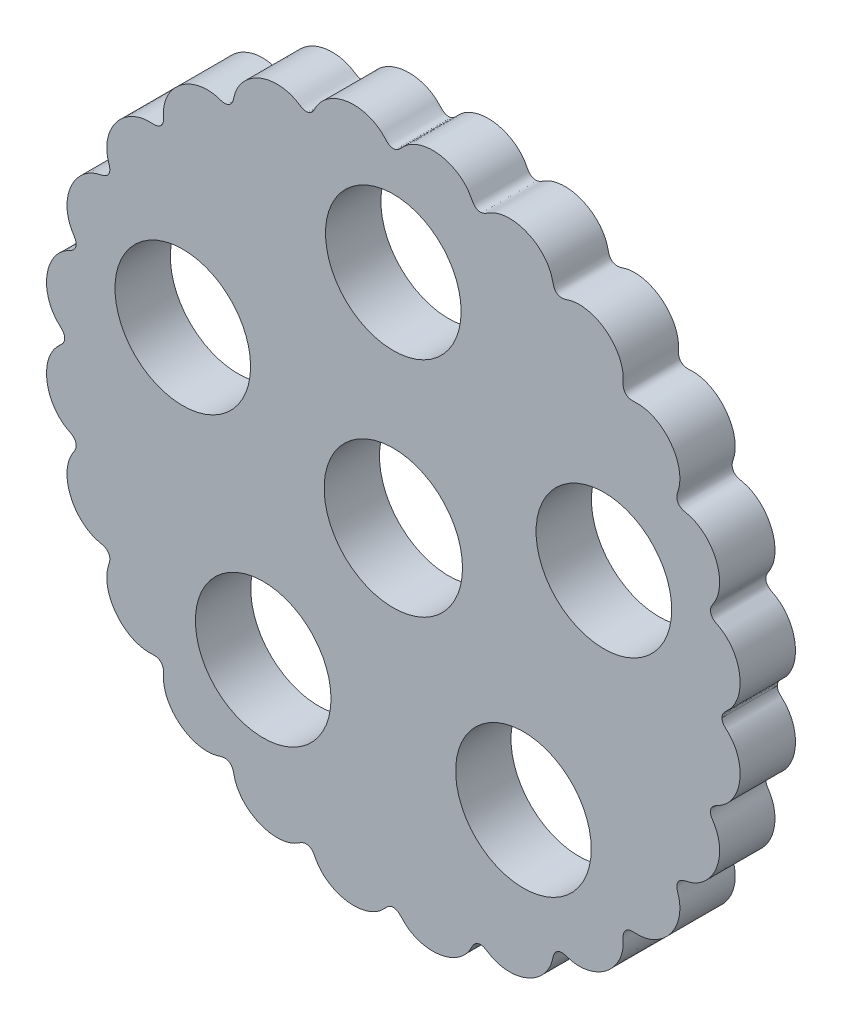
SolidWorks part; units mm, degrees
ref_plane "Plan de face" through (0, 0, 0) normal (0, 0, 1) x (1, 0, 0)
ref_plane "Plan de dessus" through (0, 0, 0) normal (0, 1, 0) x (1, 0, 0)
ref_plane "Plan de droite" through (0, 0, 0) normal (1, 0, 0) x (0, 0, -1)
sketch "Esquisse1" plane through (0, 0, 0) normal (0, 0, 1) x (1, 0, 0)
  line L0 (-1000, 0) -> (49000, 0) construction
  spline S0 degree 4 poles (22.9955, 6.6042) (22.9643, 6.5397) (22.914, 6.4032) (22.9023, 6.1862) (23.0214, 5.9244) (23.2219, 5.7605) (23.4288, 5.659) (23.6594, 5.5306) (23.9059, 5.3649) (24.1666, 5.1353) (24.4254, 4.835) (24.6422, 4.5029) (24.8162, 4.1468) (24.946, 3.7722) (25.0308, 3.385) (25.0698, 2.9906) (25.0624, 2.5943) (25.0079, 2.2017) (24.9068, 1.8224) (24.7781, 1.5066) (24.64, 1.2523) (24.5081, 1.0548) (24.3917, 0.9046) (24.2647, 0.7631) (24.1289, 0.6302) (24.012, 0.5251) (23.9248, 0.4355) (23.8688, 0.3622) (23.8363, 0.3122) (23.8082, 0.2597) (23.7852, 0.2044) (23.7697, 0.1547) (23.76, 0.1121) (23.7533, 0.0661) (23.7501, 0.0228) (23.7495, -0.004) (23.7513, -0.04) (23.7542, -0.0715) (23.7595, -0.1093) (23.7688, -0.1512) (23.7835, -0.1997) (23.8056, -0.2538) (23.8324, -0.3054) (23.8635, -0.3546) (23.9194, -0.4297) (24.009, -0.5227) (24.1313, -0.6322) (24.2737, -0.7721) (24.4392, -0.959) (24.6145, -1.2025) (24.7855, -1.5135) (24.9316, -1.8961) (25.0271, -2.299) (25.0708, -2.7153) (25.0622, -3.1311) (25.0033, -3.5401) (24.8958, -3.9363) (24.7419, -4.314) (24.5445, -4.6645) (24.307, -4.9822) (24.0331, -5.2614) (23.7654, -5.4667) (23.5164, -5.6129) (23.2956, -5.7243) (23.1195, -5.8363) (22.9763, -6.0087) (22.9044, -6.234) (22.925, -6.462) (23.0164, -6.6581) (23.1266, -6.8267) (23.2244, -6.9889) (23.3341, -7.1984) (23.4412, -7.4619) (23.5336, -7.7957) (23.5876, -8.2004) (23.5865, -8.623) (23.5267, -9.0558) (23.3808, -9.5868) (23.1436, -10.0885) (22.8209, -10.5434) (22.4327, -10.9196) (22.1006, -11.1627) (21.7948, -11.3267) (21.5321, -11.4304) (21.3065, -11.4954) (21.1232, -11.5381) (20.9306, -11.5808) (20.7385, -11.6689) (20.5325, -11.8672) (20.4495, -12.16) (20.5219, -12.4298) (20.6167, -12.7241) (20.6818, -13.0067) (20.7176, -13.3406) (20.7046, -13.7295) (20.6405, -14.1156) (20.5273, -14.4945) (20.3673, -14.8595) (20.1602, -15.2112) (19.9061, -15.5428) (19.6059, -15.8469) (19.261, -16.115) (18.8955, -16.3273) (18.5181, -16.4829) (18.1828, -16.5697) (17.9011, -16.6087) (17.6647, -16.6185) (17.4754, -16.6149) (17.2743, -16.6037) (17.0588, -16.6226) (16.851, -16.7187) (16.6918, -16.8937) (16.6141, -17.104) (16.6052, -17.3124) (16.6191, -17.5593) (16.617, -17.8481) (16.5731, -18.1826) (16.4683, -18.5594) (16.3118, -18.9239) (16.107, -19.2701) (15.8569, -19.5923) (15.5674, -19.8834) (15.2427, -20.1389) (14.8869, -20.3543) (14.5046, -20.5246) (14.1078, -20.6433) (13.7035, -20.7081) (13.2985, -20.7166) (12.9508, -20.673) (12.6603, -20.5981) (12.4161, -20.517) (12.2029, -20.4723) (11.9744, -20.5019) (11.768, -20.6211) (11.6281, -20.8042) (11.5602, -21.0112) (11.5084, -21.2632) (11.428, -21.5523) (11.2919, -21.8752) (11.082, -22.2216) (10.8237, -22.5394) (10.5226, -22.8236) (10.1839, -23.0696) (9.8195, -23.2701) (9.4358, -23.4235) (9.039, -23.5286) (8.6349, -23.5841) (8.2327, -23.5884) (7.8388, -23.5416) (7.4601, -23.444) (7.1484, -23.3148) (6.8973, -23.1723) (6.6904, -23.0367) (6.5054, -22.9402) (6.2844, -22.9024) (6.0534, -22.9528) (5.8662, -23.0846) (5.7421, -23.2618) (5.6512, -23.4416) (5.5596, -23.6073) (5.4331, -23.8072) (5.2584, -24.0316) (5.0155, -24.2786) (4.6921, -24.5276) (4.2308, -24.7924) (3.7121, -24.9769) (3.1672, -25.0695) (2.6142, -25.0665) (2.1723, -25.0046) (1.7597, -24.8871) (1.3831, -24.721) (1.0882, -24.5382) (0.867, -24.3625) (0.6979, -24.1997) (0.5693, -24.0623) (0.436, -23.9168) (0.2637, -23.7945) (-0.011, -23.7153) (-0.3061, -23.7898) (-0.5036, -23.9874) (-0.7111, -24.2166) (-0.9232, -24.4143) (-1.1945, -24.6122) (-1.5378, -24.7955) (-1.9042, -24.933) (-2.289, -25.0244) (-2.6851, -25.0684) (-3.0932, -25.0648) (-3.5074, -25.0106) (-3.9209, -24.9026) (-4.3256, -24.738) (-4.6921, -24.5276) (-5.0155, -24.2786) (-5.2584, -24.0316) (-5.4331, -23.8072) (-5.5596, -23.6073) (-5.6512, -23.4416) (-5.7421, -23.2618) (-5.8662, -23.0846) (-6.0534, -22.9528) (-6.2844, -22.9024) (-6.5054, -22.9402) (-6.6904, -23.0367) (-6.8973, -23.1723) (-7.1484, -23.3148) (-7.4601, -23.444) (-7.8388, -23.5416) (-8.2327, -23.5884) (-8.6349, -23.5841) (-9.039, -23.5286) (-9.4358, -23.4235) (-9.8195, -23.2701) (-10.1839, -23.0696) (-10.5226, -22.8236) (-10.8237, -22.5394) (-11.082, -22.2216) (-11.2919, -21.8752) (-11.428, -21.5523) (-11.5084, -21.2632) (-11.5602, -21.0112) (-11.6281, -20.8042) (-11.768, -20.6211) (-11.9744, -20.5019) (-12.2029, -20.4723) (-12.4161, -20.517) (-12.6603, -20.5981) (-12.9508, -20.673) (-13.2985, -20.7166) (-13.7035, -20.7081) (-14.1078, -20.6433) (-14.6048, -20.4946) (-15.1642, -20.2163) (-15.6552, -19.8308) (-16.055, -19.3579) (-16.3118, -18.9239) (-16.4683, -18.5594) (-16.5731, -18.1826) (-16.617, -17.8481) (-16.6191, -17.5593) (-16.6052, -17.3124) (-16.6141, -17.104) (-16.6918, -16.8937) (-16.851, -16.7187) (-17.0588, -16.6226) (-17.2743, -16.6037) (-17.4754, -16.6149) (-17.6647, -16.6185) (-17.9011, -16.6087) (-18.1828, -16.5697) (-18.5181, -16.4829) (-18.8955, -16.3273) (-19.261, -16.1151) (-19.6059, -15.8469) (-19.9061, -15.5428) (-20.1602, -15.2112) (-20.3673, -14.8595) (-20.5273, -14.4945) (-20.6405, -14.1156) (-20.7046, -13.7294) (-20.7175, -13.3407) (-20.6818, -13.0066) (-20.6166, -12.7243) (-20.522, -12.4295) (-20.4494, -12.1605) (-20.5243, -11.8962) (-20.683, -11.7227) (-20.8176, -11.632) (-20.958, -11.5755) (-21.1234, -11.5373) (-21.3064, -11.4958) (-21.5321, -11.4302) (-21.7948, -11.3268) (-22.1006, -11.1626) (-22.4327, -10.9196) (-22.7408, -10.6211) (-23.0153, -10.2693) (-23.2393, -9.8862) (-23.4104, -9.4792) (-23.5267, -9.0558) (-23.5865, -8.623) (-23.5876, -8.2004) (-23.5336, -7.7957) (-23.4412, -7.4619) (-23.3341, -7.1984) (-23.2244, -6.9889) (-23.1266, -6.8267) (-23.0164, -6.6581) (-22.925, -6.462) (-22.9044, -6.234) (-22.9763, -6.0087) (-23.1195, -5.8363) (-23.2956, -5.7243) (-23.5164, -5.6129) (-23.7654, -5.4667) (-24.0331, -5.2614) (-24.307, -4.9822) (-24.5445, -4.6645) (-24.7419, -4.314) (-24.8958, -3.9363) (-25.0033, -3.5401) (-25.0622, -3.1311) (-25.0708, -2.7153) (-25.0271, -2.299) (-24.9316, -1.8961) (-24.7855, -1.5135) (-24.6145, -1.2025) (-24.4393, -0.959) (-24.2737, -0.7721) (-24.1313, -0.6321) (-23.9982, -0.5131) (-23.8995, -0.4084) (-23.8391, -0.3182) (-23.8055, -0.2539) (-23.7835, -0.1997) (-23.7688, -0.1512) (-23.7595, -0.1093) (-23.7542, -0.0715) (-23.7513, -0.04) (-23.7495, -0.0037) (-23.7502, 0.0234) (-23.7534, 0.0677) (-23.7604, 0.1144) (-23.7705, 0.1578) (-23.7867, 0.2087) (-23.8107, 0.2649) (-23.8399, 0.3183) (-23.8736, 0.369) (-23.9317, 0.4432) (-24.0215, 0.5339) (-24.141, 0.6413) (-24.279, 0.7779) (-24.4075, 0.9235) (-24.5249, 1.0783) (-24.6575, 1.2816) (-24.7976, 1.5478) (-24.9275, 1.8824) (-25.0256, 2.2876) (-25.071, 2.7111) (-25.0623, 3.1368) (-25.0002, 3.5582) (-24.8859, 3.9683) (-24.7199, 4.3608) (-24.4999, 4.7349) (-24.2231, 5.0813) (-23.9331, 5.3469) (-23.6469, 5.5411) (-23.3456, 5.7009) (-23.0735, 5.8417) (-22.8982, 6.1368) (-22.9147, 6.4027) (-22.9638, 6.54) (-22.9956, 6.6042) knots 0 0 0 0 0 0.002762 0.005524 0.008057 0.010589 0.012487 0.014385 0.018181 0.021977 0.025773 0.029569 0.033366 0.037162 0.040959 0.044755 0.048552 0.052348 0.056144 0.059791 0.061614 0.063437 0.06526 0.067083 0.068906 0.070729 0.071301 0.071873 0.072445 0.073016 0.073588 0.07416 0.074446 0.074731 0.075303 0.075582 0.075861 0.07614 0.076419 0.076977 0.077535 0.078093 0.078652 0.07921 0.079768 0.081683 0.083599 0.085515 0.08743 0.091261 0.095093 0.099101 0.103109 0.107118 0.111126 0.115032 0.118938 0.122843 0.126749 0.130438 0.134127 0.137815 0.13966 0.141504 0.143638 0.145771 0.148068 0.150364 0.15218 0.153996 0.155812 0.157628 0.16126 0.164892 0.169075 0.173257 0.177439 0.181621 0.190162 0.194433 0.198704 0.20231 0.205917 0.20772 0.209523 0.211327 0.21313 0.215313 0.217496 0.222107 0.223949 0.225791 0.229476 0.23316 0.236844 0.240662 0.24448 0.248298 0.252116 0.256299 0.260481 0.264663 0.268845 0.272477 0.276109 0.277925 0.279741 0.281557 0.283373 0.28567 0.287966 0.2901 0.292233 0.294078 0.295922 0.299611 0.3033 0.306988 0.310894 0.3148 0.318706 0.322612 0.32662 0.330628 0.334637 0.338645 0.342476 0.346307 0.350139 0.352054 0.35397 0.356202 0.358434 0.360667 0.362899 0.364815 0.36673 0.370561 0.374393 0.378224 0.382232 0.386241 0.390249 0.394257 0.398163 0.402069 0.405975 0.40988 0.413569 0.417258 0.420947 0.422791 0.424635 0.426769 0.428902 0.431199 0.433495 0.435311 0.437127 0.438943 0.440759 0.444392 0.448024 0.452206 0.456388 0.464752 0.469023 0.473294 0.477564 0.481835 0.485441 0.489048 0.490851 0.492655 0.494458 0.496261 0.498444 0.500627 0.505239 0.507081 0.508923 0.512607 0.516291 0.519975 0.523793 0.527611 0.53143 0.535248 0.53943 0.543612 0.547794 0.551976 0.555609 0.559241 0.561057 0.562873 0.564689 0.566505 0.568801 0.571098 0.573231 0.575365 0.577209 0.579053 0.582742 0.586431 0.59012 0.594025 0.597931 0.601837 0.605743 0.609751 0.61376 0.617768 0.621776 0.625607 0.629439 0.63327 0.635186 0.637101 0.639333 0.641566 0.643798 0.64603 0.647946 0.649861 0.653693 0.657524 0.661355 0.665364 0.669372 0.677388 0.6852 0.689106 0.693012 0.6967 0.700389 0.704078 0.705922 0.707767 0.7099 0.712034 0.71433 0.716627 0.718443 0.720259 0.722075 0.723891 0.727523 0.731155 0.735337 0.739519 0.743701 0.747884 0.751702 0.75552 0.759338 0.763156 0.76684 0.770525 0.774209 0.776051 0.777893 0.782504 0.784687 0.785779 0.78687 0.788673 0.790477 0.79228 0.794083 0.79769 0.801296 0.805567 0.809838 0.814108 0.818379 0.822561 0.826743 0.830926 0.835108 0.83874 0.842372 0.844188 0.846004 0.84782 0.849636 0.851932 0.854229 0.856362 0.858496 0.86034 0.862185 0.865873 0.869562 0.873251 0.877157 0.881063 0.884968 0.888874 0.892882 0.896891 0.900899 0.904907 0.908739 0.91257 0.914486 0.916401 0.918317 0.920232 0.921349 0.921907 0.922465 0.923023 0.923581 0.92386 0.924139 0.924418 0.924697 0.925281 0.925573 0.925865 0.926449 0.927033 0.927617 0.928201 0.928785 0.929369 0.931232 0.933095 0.934957 0.93682 0.938683 0.940546 0.944272 0.94835 0.952428 0.956506 0.960584 0.964661 0.968739 0.972817 0.976894 0.98129 0.985685 0.987883 0.99008 0.994476 0.997238 1 1 1 1 1 construction
  spline S1 degree 4 poles (23.75, 0) (23.75, -0.0062) (23.7502, -0.0186) (23.7513, -0.04) (23.7542, -0.0715) (23.7595, -0.1093) (23.7688, -0.1512) (23.7835, -0.1997) (23.8056, -0.2538) (23.8324, -0.3054) (23.8635, -0.3546) (23.9194, -0.4297) (24.009, -0.5227) (24.1313, -0.6322) (24.2737, -0.7721) (24.4392, -0.959) (24.6145, -1.2025) (24.7855, -1.5135) (24.9316, -1.8961) (25.0271, -2.299) (25.0708, -2.7153) (25.0622, -3.1311) (25.0033, -3.5401) (24.8958, -3.9363) (24.7419, -4.314) (24.5445, -4.6645) (24.307, -4.9822) (24.0331, -5.2614) (23.7654, -5.4667) (23.5164, -5.6129) (23.2956, -5.7243) (23.1195, -5.8363) (22.9763, -6.0087) (22.9044, -6.234) (22.925, -6.462) (23.0164, -6.6581) (23.1266, -6.8267) (23.2244, -6.9889) (23.3341, -7.1984) (23.4412, -7.4619) (23.5336, -7.7957) (23.5876, -8.2004) (23.5865, -8.623) (23.5267, -9.0558) (23.3808, -9.5868) (23.1436, -10.0885) (22.8209, -10.5434) (22.4327, -10.9196) (22.1006, -11.1627) (21.7948, -11.3267) (21.5321, -11.4304) (21.3065, -11.4954) (21.1232, -11.5381) (20.9306, -11.5808) (20.7385, -11.6689) (20.5325, -11.8672) (20.4495, -12.16) (20.5219, -12.4298) (20.6167, -12.7241) (20.6818, -13.0067) (20.7176, -13.3406) (20.7046, -13.7295) (20.6405, -14.1156) (20.5273, -14.4945) (20.3673, -14.8595) (20.1602, -15.2112) (19.9061, -15.5428) (19.6059, -15.8469) (19.261, -16.115) (18.8955, -16.3273) (18.5181, -16.4829) (18.1828, -16.5697) (17.9011, -16.6087) (17.6647, -16.6185) (17.4754, -16.6149) (17.2743, -16.6037) (17.0588, -16.6226) (16.851, -16.7187) (16.6918, -16.8937) (16.6141, -17.104) (16.6052, -17.3124) (16.6191, -17.5593) (16.617, -17.8481) (16.5731, -18.1826) (16.4683, -18.5594) (16.3118, -18.9239) (16.107, -19.2701) (15.8569, -19.5923) (15.5674, -19.8834) (15.2427, -20.1389) (14.8869, -20.3543) (14.5046, -20.5246) (14.1078, -20.6433) (13.7035, -20.7081) (13.2985, -20.7166) (12.9508, -20.673) (12.6603, -20.5981) (12.4161, -20.517) (12.2029, -20.4723) (11.9744, -20.5019) (11.768, -20.6211) (11.6281, -20.8042) (11.5602, -21.0112) (11.5084, -21.2632) (11.428, -21.5523) (11.2919, -21.8752) (11.082, -22.2216) (10.8237, -22.5394) (10.5226, -22.8236) (10.1839, -23.0696) (9.8195, -23.2701) (9.4358, -23.4235) (9.039, -23.5286) (8.6349, -23.5841) (8.2327, -23.5884) (7.8388, -23.5416) (7.4601, -23.444) (7.1484, -23.3148) (6.8973, -23.1723) (6.6904, -23.0367) (6.5054, -22.9402) (6.2844, -22.9024) (6.0534, -22.9528) (5.8662, -23.0846) (5.7421, -23.2618) (5.6512, -23.4416) (5.5596, -23.6073) (5.4331, -23.8072) (5.2584, -24.0316) (5.0155, -24.2786) (4.6921, -24.5276) (4.2308, -24.7924) (3.7121, -24.9769) (3.1672, -25.0695) (2.6142, -25.0665) (2.1723, -25.0046) (1.7597, -24.8871) (1.3831, -24.721) (1.0882, -24.5382) (0.867, -24.3625) (0.6979, -24.1997) (0.5693, -24.0623) (0.436, -23.9168) (0.2637, -23.7945) (-0.011, -23.7153) (-0.3061, -23.7898) (-0.5036, -23.9874) (-0.7111, -24.2166) (-0.9232, -24.4143) (-1.1945, -24.6122) (-1.5378, -24.7955) (-1.9042, -24.933) (-2.289, -25.0244) (-2.6851, -25.0684) (-3.0932, -25.0648) (-3.5074, -25.0106) (-3.9209, -24.9026) (-4.3256, -24.738) (-4.6921, -24.5276) (-5.0155, -24.2786) (-5.2584, -24.0316) (-5.4331, -23.8072) (-5.5596, -23.6073) (-5.6512, -23.4416) (-5.7421, -23.2618) (-5.8662, -23.0846) (-6.0534, -22.9528) (-6.2844, -22.9024) (-6.5054, -22.9402) (-6.6904, -23.0367) (-6.8973, -23.1723) (-7.1484, -23.3148) (-7.4601, -23.444) (-7.8388, -23.5416) (-8.2327, -23.5884) (-8.6349, -23.5841) (-9.039, -23.5286) (-9.4358, -23.4235) (-9.8195, -23.2701) (-10.1839, -23.0696) (-10.5226, -22.8236) (-10.8237, -22.5394) (-11.082, -22.2216) (-11.2919, -21.8752) (-11.428, -21.5523) (-11.5084, -21.2632) (-11.5602, -21.0112) (-11.6281, -20.8042) (-11.768, -20.6211) (-11.9744, -20.5019) (-12.2029, -20.4723) (-12.4161, -20.517) (-12.6603, -20.5981) (-12.9508, -20.673) (-13.2985, -20.7166) (-13.7035, -20.7081) (-14.1078, -20.6433) (-14.6048, -20.4946) (-15.1642, -20.2163) (-15.6552, -19.8308) (-16.055, -19.3579) (-16.3118, -18.9239) (-16.4683, -18.5594) (-16.5731, -18.1826) (-16.617, -17.8481) (-16.6191, -17.5593) (-16.6052, -17.3124) (-16.6141, -17.104) (-16.6918, -16.8937) (-16.851, -16.7187) (-17.0588, -16.6226) (-17.2743, -16.6037) (-17.4754, -16.6149) (-17.6647, -16.6185) (-17.9011, -16.6087) (-18.1828, -16.5697) (-18.5181, -16.4829) (-18.8955, -16.3273) (-19.261, -16.1151) (-19.6059, -15.8469) (-19.9061, -15.5428) (-20.1602, -15.2112) (-20.3673, -14.8595) (-20.5273, -14.4945) (-20.6405, -14.1156) (-20.7046, -13.7294) (-20.7175, -13.3407) (-20.6818, -13.0066) (-20.6166, -12.7243) (-20.522, -12.4295) (-20.4494, -12.1605) (-20.5243, -11.8962) (-20.683, -11.7227) (-20.8176, -11.632) (-20.958, -11.5755) (-21.1234, -11.5373) (-21.3064, -11.4958) (-21.5321, -11.4302) (-21.7948, -11.3268) (-22.1006, -11.1626) (-22.4327, -10.9196) (-22.7408, -10.6211) (-23.0153, -10.2693) (-23.2393, -9.8862) (-23.4104, -9.4792) (-23.5267, -9.0558) (-23.5865, -8.623) (-23.5876, -8.2004) (-23.5336, -7.7957) (-23.4412, -7.4619) (-23.3341, -7.1984) (-23.2244, -6.9889) (-23.1266, -6.8267) (-23.0164, -6.6581) (-22.925, -6.462) (-22.9044, -6.234) (-22.9763, -6.0087) (-23.1195, -5.8363) (-23.2956, -5.7243) (-23.5164, -5.6129) (-23.7654, -5.4667) (-24.0331, -5.2614) (-24.307, -4.9822) (-24.5445, -4.6645) (-24.7419, -4.314) (-24.8958, -3.9363) (-25.0033, -3.5401) (-25.0622, -3.1311) (-25.0708, -2.7153) (-25.0271, -2.299) (-24.9316, -1.8961) (-24.7855, -1.5135) (-24.6145, -1.2025) (-24.4393, -0.959) (-24.2737, -0.7721) (-24.1313, -0.6321) (-23.9982, -0.5131) (-23.8995, -0.4084) (-23.8391, -0.3182) (-23.8055, -0.2539) (-23.7835, -0.1997) (-23.7688, -0.1512) (-23.7595, -0.1093) (-23.7542, -0.0715) (-23.7513, -0.04) (-23.7502, -0.0186) (-23.75, -0.0062) (-23.75, 0) knots 0.075303 0.075303 0.075303 0.075303 0.075303 0.075582 0.075861 0.07614 0.076419 0.076977 0.077535 0.078093 0.078652 0.07921 0.079768 0.081683 0.083599 0.085515 0.08743 0.091261 0.095093 0.099101 0.103109 0.107118 0.111126 0.115032 0.118938 0.122843 0.126749 0.130438 0.134127 0.137815 0.13966 0.141504 0.143638 0.145771 0.148068 0.150364 0.15218 0.153996 0.155812 0.157628 0.16126 0.164892 0.169075 0.173257 0.177439 0.181621 0.190162 0.194433 0.198704 0.20231 0.205917 0.20772 0.209523 0.211327 0.21313 0.215313 0.217496 0.222107 0.223949 0.225791 0.229476 0.23316 0.236844 0.240662 0.24448 0.248298 0.252116 0.256299 0.260481 0.264663 0.268845 0.272477 0.276109 0.277925 0.279741 0.281557 0.283373 0.28567 0.287966 0.2901 0.292233 0.294078 0.295922 0.299611 0.3033 0.306988 0.310894 0.3148 0.318706 0.322612 0.32662 0.330628 0.334637 0.338645 0.342476 0.346307 0.350139 0.352054 0.35397 0.356202 0.358434 0.360667 0.362899 0.364815 0.36673 0.370561 0.374393 0.378224 0.382232 0.386241 0.390249 0.394257 0.398163 0.402069 0.405975 0.40988 0.413569 0.417258 0.420947 0.422791 0.424635 0.426769 0.428902 0.431199 0.433495 0.435311 0.437127 0.438943 0.440759 0.444392 0.448024 0.452206 0.456388 0.464752 0.469023 0.473294 0.477564 0.481835 0.485441 0.489048 0.490851 0.492655 0.494458 0.496261 0.498444 0.500627 0.505239 0.507081 0.508923 0.512607 0.516291 0.519975 0.523793 0.527611 0.53143 0.535248 0.53943 0.543612 0.547794 0.551976 0.555609 0.559241 0.561057 0.562873 0.564689 0.566505 0.568801 0.571098 0.573231 0.575365 0.577209 0.579053 0.582742 0.586431 0.59012 0.594025 0.597931 0.601837 0.605743 0.609751 0.61376 0.617768 0.621776 0.625607 0.629439 0.63327 0.635186 0.637101 0.639333 0.641566 0.643798 0.64603 0.647946 0.649861 0.653693 0.657524 0.661355 0.665364 0.669372 0.677388 0.6852 0.689106 0.693012 0.6967 0.700389 0.704078 0.705922 0.707767 0.7099 0.712034 0.71433 0.716627 0.718443 0.720259 0.722075 0.723891 0.727523 0.731155 0.735337 0.739519 0.743701 0.747884 0.751702 0.75552 0.759338 0.763156 0.76684 0.770525 0.774209 0.776051 0.777893 0.782504 0.784687 0.785779 0.78687 0.788673 0.790477 0.79228 0.794083 0.79769 0.801296 0.805567 0.809838 0.814108 0.818379 0.822561 0.826743 0.830926 0.835108 0.83874 0.842372 0.844188 0.846004 0.84782 0.849636 0.851932 0.854229 0.856362 0.858496 0.86034 0.862185 0.865873 0.869562 0.873251 0.877157 0.881063 0.884968 0.888874 0.892882 0.896891 0.900899 0.904907 0.908739 0.91257 0.914486 0.916401 0.918317 0.920232 0.921349 0.921907 0.922465 0.923023 0.923581 0.92386 0.924139 0.924418 0.924697 0.924697 0.924697 0.924697 0.924697 construction
  spline S2 degree 4 poles (23.75, 0) (23.75, 0.0062) (23.7502, 0.0186) (23.7513, 0.04) (23.7542, 0.0715) (23.7595, 0.1093) (23.7688, 0.1512) (23.7835, 0.1997) (23.8056, 0.2538) (23.8324, 0.3054) (23.8635, 0.3546) (23.9194, 0.4297) (24.009, 0.5227) (24.1313, 0.6322) (24.2737, 0.7721) (24.4392, 0.959) (24.6145, 1.2025) (24.7855, 1.5135) (24.9316, 1.8961) (25.0271, 2.299) (25.0708, 2.7153) (25.0622, 3.1311) (25.0033, 3.5401) (24.8958, 3.9363) (24.7419, 4.314) (24.5445, 4.6645) (24.307, 4.9822) (24.0331, 5.2614) (23.7654, 5.4667) (23.5164, 5.6129) (23.2956, 5.7243) (23.1195, 5.8363) (22.9763, 6.0087) (22.9044, 6.234) (22.925, 6.462) (23.0164, 6.6581) (23.1266, 6.8267) (23.2244, 6.9889) (23.3341, 7.1984) (23.4412, 7.4619) (23.5336, 7.7957) (23.5876, 8.2004) (23.5865, 8.623) (23.5267, 9.0558) (23.3808, 9.5868) (23.1436, 10.0885) (22.8209, 10.5434) (22.4327, 10.9196) (22.1006, 11.1627) (21.7948, 11.3267) (21.5321, 11.4304) (21.3065, 11.4954) (21.1232, 11.5381) (20.9306, 11.5808) (20.7385, 11.6689) (20.5325, 11.8672) (20.4495, 12.16) (20.5219, 12.4298) (20.6167, 12.7241) (20.6818, 13.0067) (20.7176, 13.3406) (20.7046, 13.7295) (20.6405, 14.1156) (20.5273, 14.4945) (20.3673, 14.8595) (20.1602, 15.2112) (19.9061, 15.5428) (19.6059, 15.8469) (19.261, 16.115) (18.8955, 16.3273) (18.5181, 16.4829) (18.1828, 16.5697) (17.9011, 16.6087) (17.6647, 16.6185) (17.4754, 16.6149) (17.2743, 16.6037) (17.0588, 16.6226) (16.851, 16.7187) (16.6918, 16.8937) (16.6141, 17.104) (16.6052, 17.3124) (16.6191, 17.5593) (16.617, 17.8481) (16.5731, 18.1826) (16.4683, 18.5594) (16.3118, 18.9239) (16.107, 19.2701) (15.8569, 19.5923) (15.5674, 19.8834) (15.2427, 20.1389) (14.8869, 20.3543) (14.5046, 20.5246) (14.1078, 20.6433) (13.7035, 20.7081) (13.2985, 20.7166) (12.9508, 20.673) (12.6603, 20.5981) (12.4161, 20.517) (12.2029, 20.4723) (11.9744, 20.5019) (11.768, 20.6211) (11.6281, 20.8042) (11.5602, 21.0112) (11.5084, 21.2632) (11.428, 21.5523) (11.2919, 21.8752) (11.082, 22.2216) (10.8237, 22.5394) (10.5226, 22.8236) (10.1839, 23.0696) (9.8195, 23.2701) (9.4358, 23.4235) (9.039, 23.5286) (8.6349, 23.5841) (8.2327, 23.5884) (7.8388, 23.5416) (7.4601, 23.444) (7.1484, 23.3148) (6.8973, 23.1723) (6.6904, 23.0367) (6.5054, 22.9402) (6.2844, 22.9024) (6.0534, 22.9528) (5.8662, 23.0846) (5.7421, 23.2618) (5.6512, 23.4416) (5.5596, 23.6073) (5.4331, 23.8072) (5.2584, 24.0316) (5.0155, 24.2786) (4.6921, 24.5276) (4.2308, 24.7924) (3.7121, 24.9769) (3.1672, 25.0695) (2.6142, 25.0665) (2.1723, 25.0046) (1.7597, 24.8871) (1.3831, 24.721) (1.0882, 24.5382) (0.867, 24.3625) (0.6979, 24.1997) (0.5693, 24.0623) (0.436, 23.9168) (0.2637, 23.7945) (-0.011, 23.7153) (-0.3061, 23.7898) (-0.5036, 23.9874) (-0.7111, 24.2166) (-0.9232, 24.4143) (-1.1945, 24.6122) (-1.5378, 24.7955) (-1.9042, 24.933) (-2.289, 25.0244) (-2.6851, 25.0684) (-3.0932, 25.0648) (-3.5074, 25.0106) (-3.9209, 24.9026) (-4.3256, 24.738) (-4.6921, 24.5276) (-5.0155, 24.2786) (-5.2584, 24.0316) (-5.4331, 23.8072) (-5.5596, 23.6073) (-5.6512, 23.4416) (-5.7421, 23.2618) (-5.8662, 23.0846) (-6.0534, 22.9528) (-6.2844, 22.9024) (-6.5054, 22.9402) (-6.6904, 23.0367) (-6.8973, 23.1723) (-7.1484, 23.3148) (-7.4601, 23.444) (-7.8388, 23.5416) (-8.2327, 23.5884) (-8.6349, 23.5841) (-9.039, 23.5286) (-9.4358, 23.4235) (-9.8195, 23.2701) (-10.1839, 23.0696) (-10.5226, 22.8236) (-10.8237, 22.5394) (-11.082, 22.2216) (-11.2919, 21.8752) (-11.428, 21.5523) (-11.5084, 21.2632) (-11.5602, 21.0112) (-11.6281, 20.8042) (-11.768, 20.6211) (-11.9744, 20.5019) (-12.2029, 20.4723) (-12.4161, 20.517) (-12.6603, 20.5981) (-12.9508, 20.673) (-13.2985, 20.7166) (-13.7035, 20.7081) (-14.1078, 20.6433) (-14.6048, 20.4946) (-15.1642, 20.2163) (-15.6552, 19.8308) (-16.055, 19.3579) (-16.3118, 18.9239) (-16.4683, 18.5594) (-16.5731, 18.1826) (-16.617, 17.8481) (-16.6191, 17.5593) (-16.6052, 17.3124) (-16.6141, 17.104) (-16.6918, 16.8937) (-16.851, 16.7187) (-17.0588, 16.6226) (-17.2743, 16.6037) (-17.4754, 16.6149) (-17.6647, 16.6185) (-17.9011, 16.6087) (-18.1828, 16.5697) (-18.5181, 16.4829) (-18.8955, 16.3273) (-19.261, 16.1151) (-19.6059, 15.8469) (-19.9061, 15.5428) (-20.1602, 15.2112) (-20.3673, 14.8595) (-20.5273, 14.4945) (-20.6405, 14.1156) (-20.7046, 13.7294) (-20.7175, 13.3407) (-20.6818, 13.0066) (-20.6166, 12.7243) (-20.522, 12.4295) (-20.4494, 12.1605) (-20.5243, 11.8962) (-20.683, 11.7227) (-20.8176, 11.632) (-20.958, 11.5755) (-21.1234, 11.5373) (-21.3064, 11.4958) (-21.5321, 11.4302) (-21.7948, 11.3268) (-22.1006, 11.1626) (-22.4327, 10.9196) (-22.7408, 10.6211) (-23.0153, 10.2693) (-23.2393, 9.8862) (-23.4104, 9.4792) (-23.5267, 9.0558) (-23.5865, 8.623) (-23.5876, 8.2004) (-23.5336, 7.7957) (-23.4412, 7.4619) (-23.3341, 7.1984) (-23.2244, 6.9889) (-23.1266, 6.8267) (-23.0164, 6.6581) (-22.925, 6.462) (-22.9044, 6.234) (-22.9763, 6.0087) (-23.1195, 5.8363) (-23.2956, 5.7243) (-23.5164, 5.6129) (-23.7654, 5.4667) (-24.0331, 5.2614) (-24.307, 4.9822) (-24.5445, 4.6645) (-24.7419, 4.314) (-24.8958, 3.9363) (-25.0033, 3.5401) (-25.0622, 3.1311) (-25.0708, 2.7153) (-25.0271, 2.299) (-24.9316, 1.8961) (-24.7855, 1.5135) (-24.6145, 1.2025) (-24.4393, 0.959) (-24.2737, 0.7721) (-24.1313, 0.6321) (-23.9982, 0.5131) (-23.8995, 0.4084) (-23.8391, 0.3182) (-23.8055, 0.2539) (-23.7835, 0.1997) (-23.7688, 0.1512) (-23.7595, 0.1093) (-23.7542, 0.0715) (-23.7513, 0.04) (-23.7502, 0.0186) (-23.75, 0.0062) (-23.75, 0) knots 0.075303 0.075303 0.075303 0.075303 0.075303 0.075582 0.075861 0.07614 0.076419 0.076977 0.077535 0.078093 0.078652 0.07921 0.079768 0.081683 0.083599 0.085515 0.08743 0.091261 0.095093 0.099101 0.103109 0.107118 0.111126 0.115032 0.118938 0.122843 0.126749 0.130438 0.134127 0.137815 0.13966 0.141504 0.143638 0.145771 0.148068 0.150364 0.15218 0.153996 0.155812 0.157628 0.16126 0.164892 0.169075 0.173257 0.177439 0.181621 0.190162 0.194433 0.198704 0.20231 0.205917 0.20772 0.209523 0.211327 0.21313 0.215313 0.217496 0.222107 0.223949 0.225791 0.229476 0.23316 0.236844 0.240662 0.24448 0.248298 0.252116 0.256299 0.260481 0.264663 0.268845 0.272477 0.276109 0.277925 0.279741 0.281557 0.283373 0.28567 0.287966 0.2901 0.292233 0.294078 0.295922 0.299611 0.3033 0.306988 0.310894 0.3148 0.318706 0.322612 0.32662 0.330628 0.334637 0.338645 0.342476 0.346307 0.350139 0.352054 0.35397 0.356202 0.358434 0.360667 0.362899 0.364815 0.36673 0.370561 0.374393 0.378224 0.382232 0.386241 0.390249 0.394257 0.398163 0.402069 0.405975 0.40988 0.413569 0.417258 0.420947 0.422791 0.424635 0.426769 0.428902 0.431199 0.433495 0.435311 0.437127 0.438943 0.440759 0.444392 0.448024 0.452206 0.456388 0.464752 0.469023 0.473294 0.477564 0.481835 0.485441 0.489048 0.490851 0.492655 0.494458 0.496261 0.498444 0.500627 0.505239 0.507081 0.508923 0.512607 0.516291 0.519975 0.523793 0.527611 0.53143 0.535248 0.53943 0.543612 0.547794 0.551976 0.555609 0.559241 0.561057 0.562873 0.564689 0.566505 0.568801 0.571098 0.573231 0.575365 0.577209 0.579053 0.582742 0.586431 0.59012 0.594025 0.597931 0.601837 0.605743 0.609751 0.61376 0.617768 0.621776 0.625607 0.629439 0.63327 0.635186 0.637101 0.639333 0.641566 0.643798 0.64603 0.647946 0.649861 0.653693 0.657524 0.661355 0.665364 0.669372 0.677388 0.6852 0.689106 0.693012 0.6967 0.700389 0.704078 0.705922 0.707767 0.7099 0.712034 0.71433 0.716627 0.718443 0.720259 0.722075 0.723891 0.727523 0.731155 0.735337 0.739519 0.743701 0.747884 0.751702 0.75552 0.759338 0.763156 0.76684 0.770525 0.774209 0.776051 0.777893 0.782504 0.784687 0.785779 0.78687 0.788673 0.790477 0.79228 0.794083 0.79769 0.801296 0.805567 0.809838 0.814108 0.818379 0.822561 0.826743 0.830926 0.835108 0.83874 0.842372 0.844188 0.846004 0.84782 0.849636 0.851932 0.854229 0.856362 0.858496 0.86034 0.862185 0.865873 0.869562 0.873251 0.877157 0.881063 0.884968 0.888874 0.892882 0.896891 0.900899 0.904907 0.908739 0.91257 0.914486 0.916401 0.918317 0.920232 0.921349 0.921907 0.922465 0.923023 0.923581 0.92386 0.924139 0.924418 0.924697 0.924697 0.924697 0.924697 0.924697 construction
  spline S3 degree 1 poles (23.75, 0) (-23.75, 0) knots 0 0 1 1 construction
  spline S4 degree 1 poles (23.75, 0) (-23.75, 0) knots 0 0 1 1 construction
  spline S5 degree 3 poles (23.75, 0) (23.75, 0.1137) (23.8219, 0.3453) (24.0779, 0.5835) (24.3269, 0.822) (24.6131, 1.1852) (24.88, 1.7) (25.0523, 2.3737) (25.0798, 3.068) (24.9658, 3.7534) (24.714, 4.4011) (24.3299, 4.981) (23.9042, 5.3758) (23.5122, 5.6193) (23.1973, 5.7658) (22.9497, 6.022) (22.891, 6.382) (23.0374, 6.7027) (23.2955, 7.0836) (23.5106, 7.6247) (23.6065, 8.3133) (23.5489, 9.0061) (23.3498, 9.6718) (23.0199, 10.2833) (22.5707, 10.8139) (22.0159, 11.233) (21.4813, 11.4634) (21.0294, 11.5505) (20.6992, 11.6737) (20.486, 11.9701) (20.4801, 12.3255) (20.599, 12.6524) (20.7041, 13.1016) (20.726, 13.6818) (20.5875, 14.3634) (20.3076, 14.9994) (19.9035, 15.5647) (19.3931, 16.0362) (18.7949, 16.3908) (18.2422, 16.566) (17.7829, 16.6205) (17.4383, 16.613) (17.0884, 16.6008) (16.7684, 16.7684) (16.6008, 17.0884) (16.6129, 17.4383) (16.6205, 17.7829) (16.566, 18.2422) (16.3908, 18.7949) (16.0362, 19.3931) (15.5647, 19.9035) (14.9995, 20.3075) (14.3634, 20.5875) (13.6817, 20.726) (13.1016, 20.7041) (12.6522, 20.5991) (12.3259, 20.48) (11.9697, 20.4861) (11.6737, 20.6992) (11.5504, 21.0295) (11.4637, 21.4813) (11.233, 22.016) (10.814, 22.5707) (10.2832, 23.0199) (9.6718, 23.3498) (9.0061, 23.5489) (8.3132, 23.6065) (7.6247, 23.5105) (7.0835, 23.2956) (6.7027, 23.0375) (6.3819, 22.8911) (6.022, 22.9497) (5.7658, 23.1973) (5.6193, 23.5123) (5.3758, 23.9042) (4.981, 24.3299) (4.4011, 24.714) (3.7534, 24.9658) (3.068, 25.0798) (2.3737, 25.0523) (1.7, 24.88) (1.1852, 24.6131) (0.822, 24.3269) (0.5834, 24.078) (0.3446, 23.8219) (0.0001, 23.714) (-0.3442, 23.8218) (-0.5845, 24.0782) (-0.8215, 24.3267) (-1.1856, 24.6132) (-1.6999, 24.88) (-2.3737, 25.0523) (-3.068, 25.0798) (-3.7534, 24.9658) (-4.4011, 24.714) (-4.981, 24.3299) (-5.3758, 23.9042) (-5.6193, 23.5123) (-5.7658, 23.1973) (-6.022, 22.9497) (-6.3819, 22.8911) (-6.7027, 23.0375) (-7.0835, 23.2956) (-7.6247, 23.5105) (-8.3132, 23.6065) (-9.0061, 23.5489) (-9.6718, 23.3498) (-10.2832, 23.0199) (-10.814, 22.5707) (-11.233, 22.016) (-11.4637, 21.4813) (-11.5504, 21.0295) (-11.6737, 20.6992) (-11.9697, 20.4861) (-12.3259, 20.48) (-12.6522, 20.5991) (-13.1016, 20.7041) (-13.6817, 20.726) (-14.3634, 20.5875) (-14.9995, 20.3075) (-15.5647, 19.9035) (-16.0362, 19.3931) (-16.3908, 18.7949) (-16.566, 18.2422) (-16.6205, 17.7829) (-16.6129, 17.4383) (-16.6008, 17.0884) (-16.7684, 16.7684) (-17.0884, 16.6008) (-17.4383, 16.613) (-17.7829, 16.6205) (-18.2422, 16.566) (-18.7949, 16.3908) (-19.3931, 16.0362) (-19.9035, 15.5647) (-20.3076, 14.9994) (-20.5875, 14.3634) (-20.726, 13.6818) (-20.7041, 13.1016) (-20.599, 12.6524) (-20.48, 12.3256) (-20.486, 11.97) (-20.6991, 11.6738) (-21.0294, 11.5505) (-21.4813, 11.4636) (-22.0159, 11.233) (-22.5707, 10.814) (-23.0199, 10.2833) (-23.3498, 9.6718) (-23.5489, 9.0061) (-23.6065, 8.3133) (-23.5106, 7.6247) (-23.2955, 7.0836) (-23.0374, 6.7027) (-22.891, 6.382) (-22.9497, 6.022) (-23.1973, 5.7658) (-23.5122, 5.6193) (-23.9042, 5.3758) (-24.3299, 4.981) (-24.714, 4.4011) (-24.9658, 3.7534) (-25.0798, 3.068) (-25.0523, 2.3737) (-24.88, 1.7) (-24.6131, 1.1852) (-24.3269, 0.822) (-24.0779, 0.5835) (-23.8219, 0.3453) (-23.75, 0.1137) (-23.75, 0) knots 0.075303 0.075303 0.075303 0.075303 0.078621 0.081939 0.085257 0.088575 0.095211 0.101847 0.108483 0.115118 0.121754 0.12839 0.135026 0.138344 0.141662 0.14498 0.148298 0.151616 0.154934 0.16157 0.168206 0.174841 0.181477 0.188113 0.194749 0.201385 0.208021 0.211339 0.214657 0.217975 0.221293 0.224611 0.227929 0.234564 0.2412 0.247836 0.254472 0.261108 0.267744 0.27438 0.277698 0.281016 0.284334 0.287652 0.29097 0.294287 0.297605 0.300923 0.307559 0.314195 0.320831 0.327467 0.334103 0.340739 0.347375 0.350693 0.35401 0.357328 0.360646 0.363964 0.367282 0.373918 0.380554 0.38719 0.393826 0.400462 0.407098 0.413733 0.420369 0.423687 0.427005 0.430323 0.433641 0.436959 0.440277 0.446913 0.453549 0.460185 0.466821 0.473456 0.480092 0.486728 0.490046 0.493364 0.496682 0.5 0.503318 0.506636 0.509954 0.513272 0.519908 0.526544 0.533179 0.539815 0.546451 0.553087 0.559723 0.563041 0.566359 0.569677 0.572995 0.576313 0.579631 0.586267 0.592902 0.599538 0.606174 0.61281 0.619446 0.626082 0.632718 0.636036 0.639354 0.642672 0.64599 0.649308 0.652625 0.659261 0.665897 0.672533 0.679169 0.685805 0.692441 0.699077 0.702395 0.705713 0.709031 0.712348 0.715666 0.718984 0.722302 0.72562 0.732256 0.738892 0.745528 0.752164 0.7588 0.765436 0.772071 0.775389 0.778707 0.782025 0.785343 0.788661 0.791979 0.798615 0.805251 0.811887 0.818523 0.825159 0.831794 0.83843 0.845066 0.848384 0.851702 0.85502 0.858338 0.861656 0.864974 0.87161 0.878246 0.884882 0.891518 0.898153 0.904789 0.911425 0.914743 0.918061 0.921379 0.924697 0.924697 0.924697 0.924697
  spline S6 degree 3 poles (-23.75, 0) (-23.75, -0.1137) (-23.8219, -0.3453) (-24.0779, -0.5835) (-24.3269, -0.822) (-24.6131, -1.1852) (-24.88, -1.7) (-25.0523, -2.3737) (-25.0798, -3.068) (-24.9658, -3.7534) (-24.714, -4.4011) (-24.3299, -4.981) (-23.9042, -5.3758) (-23.5122, -5.6193) (-23.1973, -5.7658) (-22.9497, -6.022) (-22.891, -6.382) (-23.0374, -6.7027) (-23.2955, -7.0836) (-23.5106, -7.6247) (-23.6065, -8.3133) (-23.5489, -9.0061) (-23.3498, -9.6718) (-23.0199, -10.2833) (-22.5707, -10.814) (-22.0159, -11.233) (-21.4813, -11.4636) (-21.0294, -11.5505) (-20.6991, -11.6738) (-20.486, -11.97) (-20.48, -12.3256) (-20.599, -12.6524) (-20.7041, -13.1016) (-20.726, -13.6818) (-20.5875, -14.3634) (-20.3076, -14.9994) (-19.9035, -15.5647) (-19.3931, -16.0362) (-18.7949, -16.3908) (-18.2422, -16.566) (-17.7829, -16.6205) (-17.4383, -16.613) (-17.0884, -16.6008) (-16.7684, -16.7684) (-16.6008, -17.0884) (-16.6129, -17.4383) (-16.6205, -17.7829) (-16.566, -18.2422) (-16.3908, -18.7949) (-16.0362, -19.3931) (-15.5647, -19.9035) (-14.9995, -20.3075) (-14.3634, -20.5875) (-13.6817, -20.726) (-13.1016, -20.7041) (-12.6522, -20.5991) (-12.3259, -20.48) (-11.9697, -20.4861) (-11.6737, -20.6992) (-11.5504, -21.0295) (-11.4637, -21.4813) (-11.233, -22.016) (-10.814, -22.5707) (-10.2832, -23.0199) (-9.6718, -23.3498) (-9.0061, -23.5489) (-8.3132, -23.6065) (-7.6247, -23.5105) (-7.0835, -23.2956) (-6.7027, -23.0375) (-6.3819, -22.8911) (-6.022, -22.9497) (-5.7658, -23.1973) (-5.6193, -23.5123) (-5.3758, -23.9042) (-4.981, -24.3299) (-4.4011, -24.714) (-3.7534, -24.9658) (-3.068, -25.0798) (-2.3737, -25.0523) (-1.6999, -24.88) (-1.1856, -24.6132) (-0.8215, -24.3267) (-0.5845, -24.0782) (-0.3442, -23.8218) (0.0001, -23.714) (0.3446, -23.8219) (0.5834, -24.078) (0.822, -24.3269) (1.1852, -24.6131) (1.7, -24.88) (2.3737, -25.0523) (3.068, -25.0798) (3.7534, -24.9658) (4.4011, -24.714) (4.981, -24.3299) (5.3758, -23.9042) (5.6193, -23.5123) (5.7658, -23.1973) (6.022, -22.9497) (6.3819, -22.8911) (6.7027, -23.0375) (7.0835, -23.2956) (7.6247, -23.5105) (8.3132, -23.6065) (9.0061, -23.5489) (9.6718, -23.3498) (10.2832, -23.0199) (10.814, -22.5707) (11.233, -22.016) (11.4637, -21.4813) (11.5504, -21.0295) (11.6737, -20.6992) (11.9697, -20.4861) (12.3259, -20.48) (12.6522, -20.5991) (13.1016, -20.7041) (13.6817, -20.726) (14.3634, -20.5875) (14.9995, -20.3075) (15.5647, -19.9035) (16.0362, -19.3931) (16.3908, -18.7949) (16.566, -18.2422) (16.6205, -17.7829) (16.6129, -17.4383) (16.6008, -17.0884) (16.7684, -16.7684) (17.0884, -16.6008) (17.4383, -16.613) (17.7829, -16.6205) (18.2422, -16.566) (18.7949, -16.3908) (19.3931, -16.0362) (19.9035, -15.5647) (20.3076, -14.9994) (20.5875, -14.3634) (20.726, -13.6818) (20.7041, -13.1016) (20.599, -12.6524) (20.4801, -12.3255) (20.486, -11.9701) (20.6992, -11.6737) (21.0294, -11.5505) (21.4813, -11.4634) (22.0159, -11.233) (22.5707, -10.8139) (23.0199, -10.2833) (23.3498, -9.6718) (23.5489, -9.0061) (23.6065, -8.3133) (23.5106, -7.6247) (23.2955, -7.0836) (23.0374, -6.7027) (22.891, -6.382) (22.9497, -6.022) (23.1973, -5.7658) (23.5122, -5.6193) (23.9042, -5.3758) (24.3299, -4.981) (24.714, -4.4011) (24.9658, -3.7534) (25.0798, -3.068) (25.0523, -2.3737) (24.88, -1.7) (24.6131, -1.1852) (24.3269, -0.822) (24.0779, -0.5835) (23.8219, -0.3453) (23.75, -0.1137) (23.75, 0) knots 0.075303 0.075303 0.075303 0.075303 0.078621 0.081939 0.085257 0.088575 0.095211 0.101847 0.108483 0.115118 0.121754 0.12839 0.135026 0.138344 0.141662 0.14498 0.148298 0.151616 0.154934 0.16157 0.168206 0.174841 0.181477 0.188113 0.194749 0.201385 0.208021 0.211339 0.214657 0.217975 0.221293 0.224611 0.227929 0.234564 0.2412 0.247836 0.254472 0.261108 0.267744 0.27438 0.277698 0.281016 0.284334 0.287652 0.29097 0.294287 0.297605 0.300923 0.307559 0.314195 0.320831 0.327467 0.334103 0.340739 0.347375 0.350693 0.35401 0.357328 0.360646 0.363964 0.367282 0.373918 0.380554 0.38719 0.393826 0.400462 0.407098 0.413733 0.420369 0.423687 0.427005 0.430323 0.433641 0.436959 0.440277 0.446913 0.453549 0.460185 0.466821 0.473456 0.480092 0.486728 0.490046 0.493364 0.496682 0.5 0.503318 0.506636 0.509954 0.513272 0.519908 0.526544 0.533179 0.539815 0.546451 0.553087 0.559723 0.563041 0.566359 0.569677 0.572995 0.576313 0.579631 0.586267 0.592902 0.599538 0.606174 0.61281 0.619446 0.626082 0.632718 0.636036 0.639354 0.642672 0.64599 0.649308 0.652625 0.659261 0.665897 0.672533 0.679169 0.685805 0.692441 0.699077 0.702395 0.705713 0.709031 0.712348 0.715666 0.718984 0.722302 0.72562 0.732256 0.738892 0.745528 0.752164 0.7588 0.765436 0.772071 0.775389 0.778707 0.782025 0.785343 0.788661 0.791979 0.798615 0.805251 0.811887 0.818523 0.825159 0.831794 0.83843 0.845066 0.848384 0.851702 0.85502 0.858338 0.861656 0.864974 0.87161 0.878246 0.884882 0.891518 0.898153 0.904789 0.911425 0.914743 0.918061 0.921379 0.924697 0.924697 0.924697 0.924697
  dimension "D2" = 0
extrude "Boss.-Extru.1" add sketch "Esquisse1" along normal blind 4
sketch "Esquisse2" plane through (0, 0, 4) normal (0, 0, 1) x (1, 0, 0)
  circle A0 centre (0, 0) radius 5
  circle A1 centre (0, 16) radius 4.9
  circle A2 centre (15.2169, 4.9443) radius 4.9
  circle A3 centre (9.4046, -12.9443) radius 4.9
  circle A4 centre (-9.4046, -12.9443) radius 4.9
  circle A5 centre (-15.2169, 4.9443) radius 4.9
  point P15 (0, 0)
  dimension "D1" = 10
  dimension "D2" = 9.8
  dimension "D3" = 16
  dimension "D4" = 5
extrude "Enlèv. mat.-Extru.1" cut sketch "Esquisse2" against normal through all
equation "\"R\"= 25'Radius of the rotor"
equation "\"E\"= 0.75'Eccentricity from input shaft to center of rotor"
equation "\"Rr\"= 0.5'Roller radius"
equation "\"N\"= 25'Amount of rollers"
